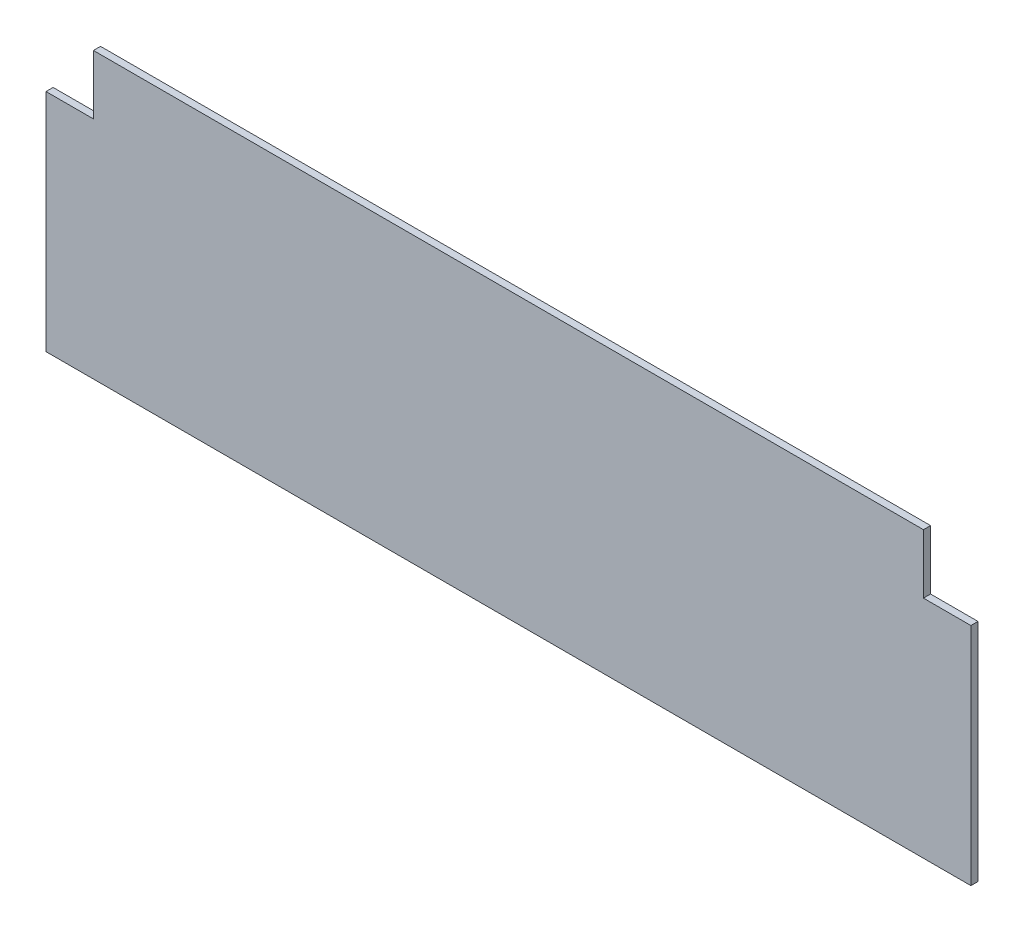
SolidWorks part; units mm, degrees
ref_plane "前视基准面" through (0, 0, 0) normal (0, 0, 1) x (1, 0, 0)
ref_plane "上视基准面" through (0, 0, 0) normal (0, 1, 0) x (1, 0, 0)
ref_plane "右视基准面" through (0, 0, 0) normal (1, 0, 0) x (0, 0, -1)
other "Configuration Table"
sketch "草图1" plane through (0, 0, 0) normal (0, 0, 1) x (1, 0, 0)
  line L1 (20, 5) -> (370, 5)
  line L2 (0, -20) -> (0, -115)
  line L3 (0, -115) -> (390, -115)
  line L4 (390, -20) -> (390, -115)
  line L7 (390, -20) -> (370, -20)
  line L8 (370, 5) -> (370, -20)
  line L11 (0, -20) -> (20, -20)
  line L12 (20, 5) -> (20, -20)
  dimension "D1" = 350
  dimension "D2" = 120
  dimension "D3" = 25
  dimension "D4" = 20
  dimension "D5" = 25
  dimension "D6" = 20
  dimension "D7" = 95
  dimension "D8" = 95
extrude "凸台-拉伸1" add sketch "草图1" along normal blind 3
